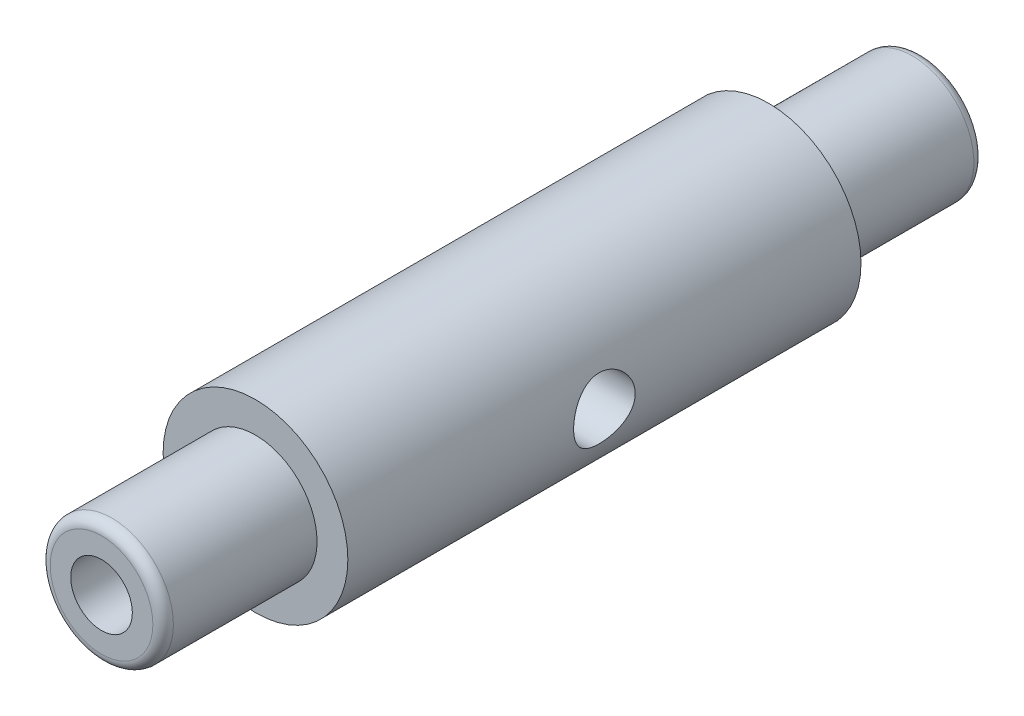
SolidWorks part; units mm, degrees
ref_plane "Front Plane" through (0, 0, 0) normal (0, 0, 1) x (1, 0, 0)
ref_plane "Top Plane" through (0, 0, 0) normal (0, 1, 0) x (1, 0, 0)
ref_plane "Right Plane" through (0, 0, 0) normal (1, 0, 0) x (0, 0, -1)
sketch "Sketch1" plane through (0, 0, 0) normal (1, 0, 0) x (0, 0, -1)
  line L0 (-40, 0) -> (-40, 6)
  line L1 (-40, 6) -> (-25, 6)
  line L2 (-25, 6) -> (-25, 9)
  line L3 (-25, 9) -> (25, 9)
  line L4 (25, 9) -> (25, 6)
  line L5 (25, 6) -> (40, 6)
  line L6 (40, 6) -> (40, 0)
  line L7 (40, 0) -> (-40, 0)
  line L8 (0, 0) -> (0, 55.1064) construction
  dimension "D1" = 80
  dimension "D2" = 50
  dimension "D3" = 6
  dimension "D4" = 6
  dimension "D5" = 9
revolve "Revolve1" add sketch "Sketch1" angle 360 about L7
fillet "Fillet1" radius 1 2 edges at (-6, 0, -40) (-6, 0, 40)
hole_wizard "Hole1" positions "Sketch7" profile "Sketch8" legacy
sketch "Sketch7" plane through (0, 0, 40) normal (0, 0, 1) x (1, 0, 0)
  point P0 (0, 0)
sketch "Sketch8" plane through (0, 0, 40) normal (1, 0, 0) x (0, -1, 0)
  line L0 (0, 0) -> (0, 45)
  line L1 (0, 45) -> (3, 45)
  line L2 (3, 45) -> (3, 0)
  line L3 (3, 0) -> (0, 0)
  line L4 (0, 110) -> (0, -10) construction
  dimension "Diameter" = 6
  dimension "Depth" = 45
sketch "Sketch9" plane through (0, 0, 0) normal (1, 0, 0) x (0, 0, -1)
  circle A0 centre (0, 0) radius 3
  dimension "D1" = 6
extrude "Cut-Extrude1" cut sketch "Sketch9" against normal through all both and the other way through all
